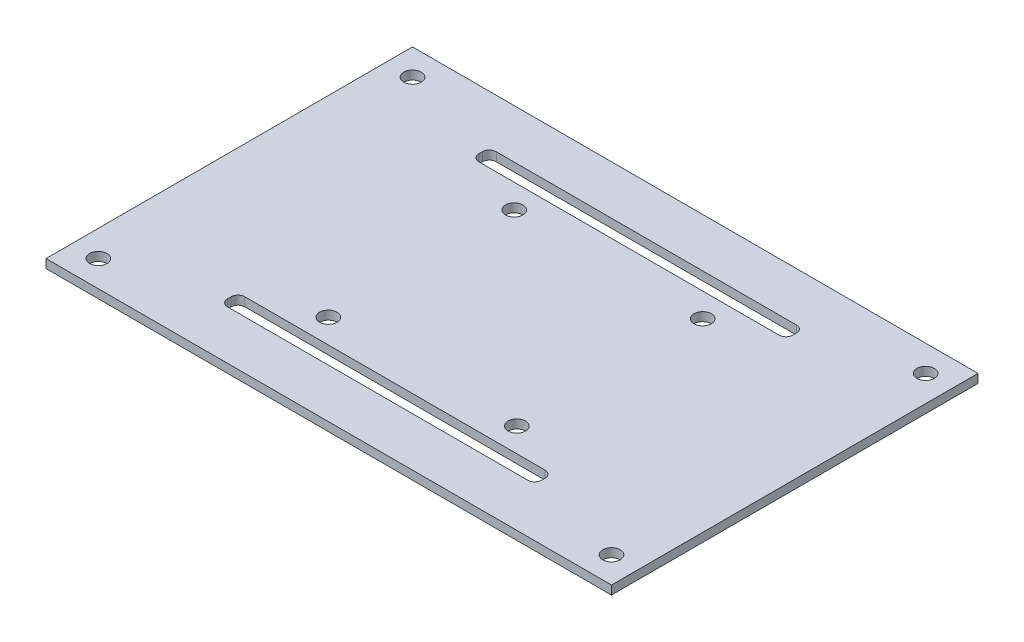
SolidWorks part; units mm, degrees
material "6061-T6 (SS)"
ref_plane "Front Plane" through (0, 0, 0) normal (0, 0, 1) x (1, 0, 0)
ref_plane "Top Plane" through (0, 0, 0) normal (0, 1, 0) x (1, 0, 0)
ref_plane "Right Plane" through (0, 0, 0) normal (1, 0, 0) x (0, 0, -1)
sketch "Sketch1" plane through (0, 0, 0) normal (0, 1, 0) x (1, 0, 0)
  line L1 (-102.87, -66.675) -> (102.87, -66.675)
  line L2 (-102.87, -66.675) -> (-102.87, 66.675)
  line L3 (-102.87, 66.675) -> (102.87, 66.675)
  line L4 (102.87, -66.675) -> (102.87, 66.675)
  line L5 (-102.87, -66.675) -> (102.87, 66.675) construction
  line L6 (-102.87, 66.675) -> (102.87, -66.675) construction
  point P0 (0, 0)
  dimension "D1" = 133.35
  dimension "D2" = 205.74
extrude "Boss-Extrude1" add sketch "Sketch1" along normal blind 3.175 contours L3 L4 L1 L2
sketch "Sketch3" plane through (0, 3.175, 0) normal (0, 1, 0) x (1, 0, 0)
  line L0 (102.87, -66.675) -> (102.87, 66.675) construction
  line L2 (35.56, -33.8125) -> (-33.02, -33.8125)
  line L3 (35.56, -33.8125) -> (35.56, 33.8125)
  line L4 (35.56, 33.8125) -> (-33.02, 33.8125)
  line L5 (-33.02, -33.8125) -> (-33.02, 33.8125)
  line L6 (35.56, -33.8125) -> (-33.02, 33.8125) construction
  line L7 (35.56, 33.8125) -> (-33.02, -33.8125) construction
  circle A7 centre (35.56, 33.8125) radius 3.175
  circle A8 centre (35.56, -33.8125) radius 3.175
  circle A9 centre (-33.02, -33.8125) radius 3.175
  circle A10 centre (-33.02, 33.8125) radius 3.175
  point P0 (1.27, 0)
  dimension "D3" = 0
  dimension "D4" = 6.35
  dimension "D5" = 6.35
  dimension "D6" = 6.35
  dimension "D7" = 6.35
  dimension "D1" = 68.58
  dimension "D2" = 67.625
  dimension "D8" = 101.6
extrude "Cut-Extrude3" cut sketch "Sketch3" against normal through all contours A9 | A8 | A7 | A10
sketch "Sketch4" plane through (0, 3.175, 0) normal (0, 1, 0) x (1, 0, 0)
  line L1 (-102.87, -66.675) -> (-102.87, 66.675) construction
  line L2 (102.87, -66.675) -> (102.87, 66.675) construction
  line L3 (-102.87, 0) -> (102.87, 0) construction
  line L4 (-102.87, 66.675) -> (102.87, 66.675) construction
  circle A10 centre (-93.345, 57.15) radius 3.175
  circle A11 centre (93.345, 57.15) radius 3.175
  circle A12 centre (93.345, -57.15) radius 3.175
  circle A13 centre (-93.345, -57.15) radius 3.175
  dimension "D1" = 9.525
  dimension "D4" = 6.35
  dimension "D3" = 6.35
  dimension "D2" = 9.525
  dimension "D5" = 9.525
  dimension "D6" = 9.525
extrude "Cut-Extrude4" cut sketch "Sketch4" against normal through all
sketch "Sketch5" plane through (0, 3.175, 0) normal (0, 1, 0) x (1, 0, 0)
  line L0 (-102.87, -66.675) -> (102.87, -66.675) construction
  line L1 (-54.61, -42.545) -> (54.61, -42.545)
  line L2 (-57.15, -45.085) -> (-57.15, -46.355)
  line L3 (-54.61, -48.895) -> (54.61, -48.895)
  line L4 (57.15, -45.085) -> (57.15, -46.355)
  line L5 (-102.87, 0) -> (102.87, 0) construction
  line L6 (-102.87, -66.675) -> (-102.87, 66.675) construction
  line L7 (102.87, -66.675) -> (102.87, 66.675) construction
  line L8 (57.15, 45.085) -> (57.15, 46.355)
  line L9 (-54.61, 48.895) -> (54.61, 48.895)
  line L10 (-57.15, 45.085) -> (-57.15, 46.355)
  line L11 (-54.61, 42.545) -> (54.61, 42.545)
  arc A0 (54.61, -42.545) -> (57.15, -45.085) centre (54.61, -45.085) cw
  arc A1 (54.61, -48.895) -> (57.15, -46.355) centre (54.61, -46.355) ccw
  arc A2 (-57.15, -46.355) -> (-54.61, -48.895) centre (-54.61, -46.355) ccw
  arc A3 (-54.61, -42.545) -> (-57.15, -45.085) centre (-54.61, -45.085) ccw
  arc A4 (-54.61, 42.545) -> (-57.15, 45.085) centre (-54.61, 45.085) cw
  arc A5 (-57.15, 46.355) -> (-54.61, 48.895) centre (-54.61, 46.355) cw
  arc A6 (54.61, 48.895) -> (57.15, 46.355) centre (54.61, 46.355) cw
  arc A7 (54.61, 42.545) -> (57.15, 45.085) centre (54.61, 45.085) ccw
  point P6 (0, -42.545)
  point P12 (57.15, -48.895)
  point P15 (-57.15, -48.895)
  point P18 (-57.15, -42.545)
  point P37 (-57.15, 42.545)
  point P38 (-57.15, 48.895)
  point P39 (57.15, 48.895)
  dimension "D6" = 2.54
  dimension "D1" = 17.78
  dimension "D2" = 6.35
  dimension "D3" = 24.13
  dimension "D4" = 114.3
  dimension "D5" = 0
extrude "Cut-Extrude5" cut sketch "Sketch5" against normal through all
